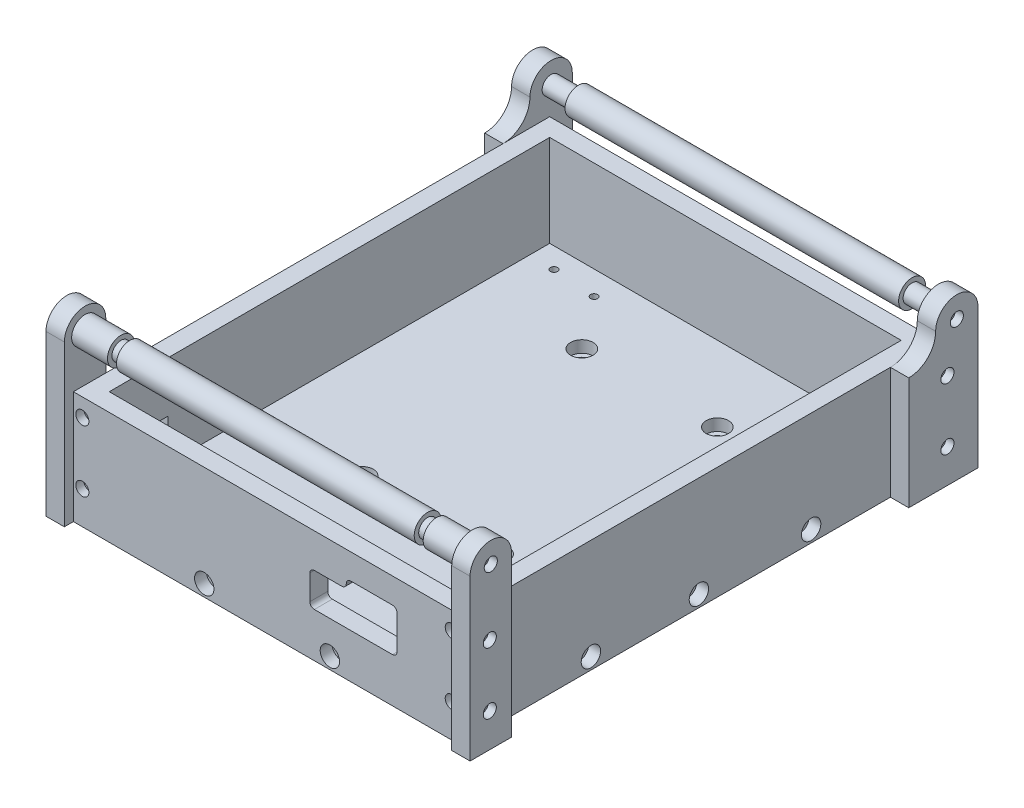
SolidWorks part; units mm, degrees
ref_plane "Front Plane" through (0, 0, 0) normal (0, 0, 1) x (1, 0, 0)
ref_plane "Top Plane" through (0, 0, 0) normal (0, 1, 0) x (1, 0, 0)
ref_plane "Right Plane" through (0, 0, 0) normal (1, 0, 0) x (0, 0, -1)
sketch "Sketch1" plane through (0, 0, 0) normal (0, 1, 0) x (1, 0, 0)
  line L1 (0, 0) -> (114.5, 0) construction
  line L2 (0, 0) -> (0, 146) construction
  line L3 (0, 146) -> (114.5, 146) construction
  line L4 (114.5, 0) -> (114.5, 146) construction
  line L8 (-5, 151) -> (119.5, 151)
  line L9 (119.5, -5) -> (119.5, 151)
  line L10 (-5, -5) -> (119.5, -5)
  line L11 (-5, -5) -> (-5, 151)
  line L12 (-11.35, 157.35) -> (125.85, 157.35)
  line L13 (125.85, -11.35) -> (125.85, 157.35)
  line L14 (-11.35, -11.35) -> (125.85, -11.35)
  line L15 (-11.35, -11.35) -> (-11.35, 157.35)
  dimension "D1" = 114.5
  dimension "D2" = 146
  dimension "D3" = 6.35
  dimension "D4" = 5
extrude "Boss-Extrude1" add sketch "Sketch1" against normal blind 6.35 contours L15 L12 L13 L14
sketch "Sketch3" plane through (0, 0, 0) normal (0, 1, 0) x (1, 0, 0)
  line L4 (-5, 151) -> (119.5, 151)
  line L5 (119.5, -5) -> (119.5, 151)
  line L6 (-5, -5) -> (119.5, -5)
  line L7 (-5, -5) -> (-5, 151)
  line L8 (-11.35, 157.35) -> (125.85, 157.35)
  line L9 (125.85, -11.35) -> (125.85, 157.35)
  line L10 (-11.35, -11.35) -> (125.85, -11.35)
  line L11 (-11.35, -11.35) -> (-11.35, 157.35)
  line L12 (-11.35, -11.35) -> (-11.35, 157.35) construction
  line L13 (-11.35, 157.35) -> (125.85, 157.35) construction
  line L14 (-11.35, -11.35) -> (125.85, -11.35) construction
  line L15 (-5, 151) -> (-11.35, 151) construction
  line L16 (-5, -5) -> (-11.35, -5) construction
  line L17 (119.5, -5) -> (125.85, -5) construction
  line L18 (119.5, 151) -> (125.85, 151) construction
  dimension "D1" = 6.35
  dimension "D2" = 6.35
  dimension "D3" = 6.35
  dimension "D4" = 6.35
extrude "Boss-Extrude2" add sketch "Sketch3" along normal blind 32.5 and the other way blind 7.35
sketch "Sketch4" plane through (0, 0, 11.35) normal (0, 0, 1) x (1, 0, 0)
  line L0 (-11.35, -7.35) -> (-11.35, 32.5) construction
  line L1 (-11.35, 32.5) -> (125.85, 32.5) construction
  line L3 (119.5, 0) -> (119.5, 32.5) construction
  line L4 (-5, 0) -> (119.5, 0) construction
  line L5 (-5, -7.35) -> (-5, -6.35) construction
  line L6 (119.5, -7.35) -> (119.5, -6.35) construction
  circle A0 centre (-8.175, 26.15) radius 1.1906 construction
  circle A2 centre (35, -3.175) radius 1.7859
  circle A3 centre (79.5, -3.175) radius 1.7859
  circle A4 centre (122.675, 26.15) radius 1.1906 construction
  circle A6 centre (-8.175, 4.325) radius 1.1906 construction
  circle A7 centre (122.675, 4.325) radius 1.1906 construction
  dimension "D2" = 2.3813
  dimension "D3" = 3.5719
  dimension "D1" = 3.175
  dimension "D4" = 6.35
  dimension "D6" = 3.175
  dimension "D7" = 21.825
  dimension "D8" = 3.175
  dimension "D9" = 40
  dimension "D10" = 40
hole_wizard "CBORE for #0 Socket Head Cap Screw1" positions "3DSketch1" profile "Sketch6" counterbore size "#0" standard "ANSI Inch"
sketch3d "3DSketch1"
  point P0 (-8.175, 26.15, 11.35)
  point P3 (-8.175, 4.325, 11.35)
  point P9 (122.675, 26.15, 11.35)
  point P12 (122.675, 4.325, 11.35)
sketch "Sketch6" plane through (-8.175, 26.15, 11.35) normal (1, 0, 0) x (0, -1, 0)
  line L0 (0, 0) -> (0, 10.7654)
  line L1 (0, 10.7654) -> (1.1906, 10.05)
  line L2 (1.1906, 10.05) -> (1.1906, 2.8448)
  line L3 (1.1906, 2.8448) -> (2.3241, 2.8448)
  line L4 (2.3241, 2.8448) -> (2.3241, 0)
  line L5 (2.3241, 0) -> (0, 0)
  line L10 (0, 10.7654) -> (-1.1906, 10.05) construction
  line L11 (0, -6.35) -> (0, 107.95) construction
  dimension "Hole Dia." = 2.3812
  dimension "Hole Depth" = 10.05
  dimension "C'Bore Dia." = 4.6482
  dimension "C'Bore Depth" = 2.8448
  dimension "Drill Angle" = 118
sketch "Sketch7" plane through (125.85, 0, 0) normal (1, 0, 0) x (0, 0, -1)
  line L0 (-5, 0) -> (-5, 32.5) construction
  line L1 (-11.35, -1.3891) -> (-11.35, -4.9609) construction
  line L2 (-5, 0) -> (151, 0) construction
  circle A0 centre (34.75, -3.175) radius 1.7859
  circle A1 centre (112.75, -3.175) radius 1.7859
  circle A2 centre (73, -3.175) radius 1.7859
  point P6 (-11.35, -3.175)
  point P11 (73, 0)
  dimension "D1" = 3.5719
  dimension "D3" = 39.75
  dimension "D4" = 39.75
hole_wizard "CBORE for #0 Socket Head Cap Screw2" positions "3DSketch2" profile "Sketch8" counterbore size "#0" standard "ANSI Inch"
sketch3d "3DSketch2"
  point P0 (125.85, -3.175, -34.75)
  point P3 (125.85, -3.175, -73)
  point P6 (125.85, -3.175, -112.75)
  point P10 (35, -3.175, 11.35)
  point P13 (79.5, -3.175, 11.35)
sketch "Sketch8" plane through (125.85, -3.175, -34.75) normal (0, 1, 0) x (0, 0, -1)
  line L0 (0, 0) -> (0, 11.1231)
  line L1 (0, 11.1231) -> (1.7859, 10.05)
  line L2 (1.7859, 10.05) -> (1.7859, 4.1656)
  line L3 (1.7859, 4.1656) -> (3.429, 4.1656)
  line L4 (3.429, 4.1656) -> (3.429, 0)
  line L5 (3.429, 0) -> (0, 0)
  line L10 (0, 11.1231) -> (-1.7859, 10.05) construction
  line L11 (0, -6.35) -> (0, 107.95) construction
  dimension "Hole Dia." = 3.5719
  dimension "Hole Depth" = 10.05
  dimension "C'Bore Dia." = 6.858
  dimension "C'Bore Depth" = 4.1656
  dimension "Drill Angle" = 118
sketch "Sketch9" plane through (125.85, 0, 0) normal (1, 0, 0) x (0, 0, -1)
  line L5 (-14.546, -7.35) -> (0.1332, -7.35)
  line L6 (-14.546, -7.35) -> (-14.546, 49.35)
  line L9 (140.825, -7.35) -> (157.35, -7.35)
  line L11 (157.35, -7.35) -> (157.35, 1.02) construction
  line L12 (157.35, -7.35) -> (157.35, 32.5) construction
  line L14 (-8.5052, 27.3406) -> (-8.5052, 24.9594) construction
  line L15 (-8.5052, 6.6491) -> (-8.5052, 2.0009) construction
  line L16 (-11.35, 32.5) -> (157.35, 32.5) construction
  line L20 (165.35, -7.35) -> (165.35, 42.025)
  line L21 (140.825, 32.5) -> (140.825, -7.35)
  line L22 (0.1332, -7.35) -> (0.1332, 49.35)
  line L23 (157.35, -7.35) -> (165.35, -7.35)
  circle A3 centre (-7.2064, 49.35) radius 3.175 construction
  arc A11 (140.825, 32.5) -> (150.35, 42.025) centre (140.825, 42.025) ccw
  circle A12 centre (157.85, 42.025) radius 3.175 construction
  arc A13 (150.35, 42.025) -> (165.35, 42.025) centre (157.85, 42.025) cw
  arc A14 (-14.546, 49.35) -> (0.1332, 49.35) centre (-7.2064, 49.35) cw
  point P18 (-8.5052, 26.15)
  point P19 (-8.5052, 4.325)
  point P22 (154.175, 26.15)
  point P25 (154.175, 4.325)
  dimension "D1" = 6.35
  dimension "D2" = 7.5
  dimension "D3" = 9.525
  dimension "D6" = 6.35
  dimension "D8" = 39.85
  dimension "D4" = 0.5
  dimension "D5" = 3.175
  dimension "D7" = 16.85
extrude "Boss-Extrude3" add sketch "Sketch9" along normal blind 6.4979
sketch "Sketch10" plane through (0, 0, 0) normal (0, 1, 0) x (1, 0, 0)
  line L0 (57.25, -5) -> (57.25, 50.041) construction
  line L1 (-5, -5) -> (119.5, -5) construction
ref_plane "Plane1" through (57.25, 0, 0) normal (1, 0, 0) x (0, 0, -1)
mirror "Mirror1" about plane through (57.25, 0, 0) normal (1, 0, 0) of "Boss-Extrude3"
sketch "Sketch11" plane through (-17.8479, 0, 0) normal (-1, 0, 0) x (0, 0, 1)
  circle A0 centre (7.2064, 49.35) radius 3.175
extrude "Boss-Extrude4" add sketch "Sketch11" against normal up to surface (150.1957 mm away) up to face at (132.3479, 22.8349, 7.2064)
sketch "Sketch13" plane through (132.3479, 0, 0) normal (1, 0, 0) x (0, 0, -1)
  circle A0 centre (157.85, 42.025) radius 3.175
  arc A1 (165.35, 42.025) -> (150.35, 42.025) centre (157.85, 42.025) ccw construction
  dimension "D1" = 6.35
extrude "Boss-Extrude5" add sketch "Sketch13" against normal up to surface (150.1957 mm away) up to face at (-17.8479, 21.4755, -152.9345)
sketch "Sketch15" plane through (132.3479, 0, 0) normal (1, 0, 0) x (0, 0, -1)
  circle A0 centre (157.85, 42.025) radius 4.7625
  arc A1 (165.35, 42.025) -> (150.35, 42.025) centre (157.85, 42.025) ccw construction
  dimension "D1" = 9.525
extrude "Boss-Extrude6" add sketch "Sketch15" against normal blind 118.15 from offset 15.85 offset against normal yes
hole_wizard "CBORE for #0 Socket Head Cap Screw3" positions "3DSketch3" profile "Sketch16" counterbore size "#0" standard "ANSI Inch"
sketch3d "3DSketch3"
  line L4 (132.3479, 49.35, 7.2064) -> (125.85, 49.35, 7.2064) construction
  line L5 (132.3479, 42.025, -157.85) -> (125.85, 42.025, -157.85) construction
  line L9 (132.3479, 49.35, 14.546) -> (132.3479, -7.35, 14.546) construction
  line L10 (132.3479, 49.35, 14.546) -> (132.3479, -7.35, 14.546)
  line L11 (132.3479, 32.5, -154.5249) -> (122.9136, 32.5, -154.5249) construction
  line L14 (119.5, 32.5, -151) -> (-5, 32.5, -151) construction
  point P17 (132.3479, 49.35, 7.2064)
  point P21 (132.3479, 42.025, -157.85)
  point P87 (132.3479, 26.3157, 7.5566)
  point P89 (132.3479, 4.5437, 7.5566)
  point P105 (132.3479, 26.3157, -154.5249)
  point P107 (132.3479, 4.5437, -154.5249)
  dimension "D1" = 3.5249
sketch "Sketch16" plane through (132.3479, 49.35, 7.2064) normal (0, 1, 0) x (0, 0, -1)
  line L0 (0, 0) -> (0, 10.7654)
  line L1 (0, 10.7654) -> (1.1906, 10.05)
  line L2 (1.1906, 10.05) -> (1.1906, 2.8448)
  line L3 (1.1906, 2.8448) -> (2.3241, 2.8448)
  line L4 (2.3241, 2.8448) -> (2.3241, 0)
  line L5 (2.3241, 0) -> (0, 0)
  line L10 (0, 10.7654) -> (-1.1906, 10.05) construction
  line L11 (0, -6.35) -> (0, 107.95) construction
  dimension "Hole Dia." = 2.3812
  dimension "Hole Depth" = 10.05
  dimension "C'Bore Dia." = 4.6482
  dimension "C'Bore Depth" = 2.8448
  dimension "Drill Angle" = 118
sketch "Sketch19" plane through (0, 0, 0) normal (0, 1, 0) x (1, 0, 0)
  line L0 (119.5, 151) -> (-5, 151) construction
  line L1 (14.51, 146.55) -> (99.99, 146.55) construction
  line L2 (14.51, 146.55) -> (14.51, 18.79) construction
  line L3 (14.51, 18.79) -> (99.99, 18.79) construction
  line L4 (99.99, 146.55) -> (99.99, 18.79) construction
  line L5 (57.25, -5) -> (57.25, 50.041) construction
  point P6 (33.0427, 124.3411)
  point P7 (81.0329, 124.3411)
  point P8 (81.0329, 46.5266)
  point P9 (33.0427, 46.5266)
  dimension "D1" = 4.45
  dimension "D2" = 85.48
  dimension "D3" = 127.76
  dimension "D4" = 42.74
hole_wizard "CBORE for #8 Socket Head Cap Screw1" positions "Sketch20" profile "Sketch21" counterbore size "#8" standard "ANSI Inch"
sketch "Sketch20" plane through (0, 0, 0) normal (0, 1, 0) x (1, 0, 0)
  point P0 (33.0427, 124.3411)
  point P3 (81.0329, 124.3411)
  point P6 (81.0329, 46.5266)
  point P9 (33.0427, 46.5266)
sketch "Sketch21" plane through (33.0427, 0, -124.3411) normal (1, 0, 0) x (0, 0, 1)
  line L0 (0, 0) -> (0, 11.4007)
  line L1 (0, 11.4007) -> (2.2479, 10.05)
  line L2 (2.2479, 10.05) -> (2.2479, 4.1656)
  line L3 (2.2479, 4.1656) -> (3.9688, 4.1656)
  line L4 (3.9688, 4.1656) -> (3.9688, 0)
  line L5 (3.9688, 0) -> (0, 0)
  line L10 (0, 11.4007) -> (-2.2479, 10.05) construction
  line L11 (0, -6.35) -> (0, 107.95) construction
  dimension "Hole Dia." = 4.4958
  dimension "Hole Depth" = 10.05
  dimension "C'Bore Dia." = 7.9375
  dimension "C'Bore Depth" = 4.1656
  dimension "Drill Angle" = 118
sketch "Sketch22" plane through (0, 0, 11.35) normal (0, 0, 1) x (1, 0, 0)
  line L0 (82.912, 18.778) -> (73.9904, 18.778) construction
  line L10 (57.25, 32.5) -> (57.25, -11.4472) construction
  line L11 (-11.35, 32.5) -> (125.85, 32.5) construction
  line L12 (82.912, 20.3655) -> (73.9904, 20.3655)
  line L13 (72.4029, 18.778) -> (72.4029, 9.9676)
  line L15 (-0.034, 5) -> (-0.034, 6.6) construction
  line L19 (114.52, 5) -> (114.52, 6.6) construction
  line L20 (-0.034, 6.6) -> (114.52, 6.6) construction
  line L21 (-0.034, 5) -> (114.52, 5) construction
  line L23 (73.9904, 8.3801) -> (101.668, 8.3801)
  line L26 (103.2555, 9.9676) -> (103.2555, 21.9697)
  line L27 (101.668, 23.5572) -> (86.89, 23.5572)
  line L28 (85.3025, 21.953) -> (85.3025, 21.9697)
  line L29 (82.912, 20.3655) -> (83.715, 20.3655)
  line L30 (119.5, 19.6927) -> (119.5, 3.1627) construction
  line L31 (125.85, -7.35) -> (125.85, 32.5) construction
  line L32 (14.51, 0) -> (99.99, 0) construction
  line L33 (73.9904, 18.778) -> (73.9904, 9.9676) construction
  line L34 (73.9904, 9.9676) -> (101.668, 9.9676) construction
  line L35 (101.668, 9.9676) -> (101.668, 21.9697) construction
  line L36 (101.668, 21.9697) -> (86.89, 21.9697) construction
  line L37 (86.89, 21.953) -> (86.89, 21.9697) construction
  line L38 (82.912, 18.778) -> (83.715, 18.778) construction
  arc A12 (73.9904, 20.3655) -> (72.4029, 18.778) centre (73.9904, 18.778) ccw
  arc A13 (72.4029, 9.9676) -> (73.9904, 8.3801) centre (73.9904, 9.9676) ccw
  arc A14 (103.2555, 9.9676) -> (101.668, 8.3801) centre (101.668, 9.9676) cw
  arc A15 (101.668, 23.5572) -> (103.2555, 21.9697) centre (101.668, 21.9697) cw
  arc A16 (86.89, 23.5572) -> (85.3025, 21.9697) centre (86.89, 21.9697) ccw
  arc A17 (83.715, 20.3655) -> (85.3025, 21.953) centre (83.715, 21.953) ccw
  arc A18 (73.9904, 18.778) -> (73.9904, 18.778) centre (73.9904, 18.778) ccw construction
  arc A19 (73.9904, 9.9676) -> (73.9904, 9.9676) centre (73.9904, 9.9676) ccw construction
  arc A20 (101.668, 9.9676) -> (101.668, 9.9676) centre (101.668, 9.9676) cw construction
  arc A21 (101.668, 21.9697) -> (101.668, 21.9697) centre (101.668, 21.9697) cw construction
  arc A22 (86.89, 21.9697) -> (86.89, 21.9697) centre (86.89, 21.9697) ccw construction
  arc A23 (83.715, 18.778) -> (86.89, 21.953) centre (83.715, 21.953) ccw construction
  point P7 (103.2555, 15.9686)
  point P10 (41.9707, 6.6)
  point P13 (42.0971, 20.3655)
  point P28 (0, 0)
  dimension "D5" = 5
  dimension "D1" = 114.554
  dimension "D2" = 6.35
  dimension "D3" = 4.98
  dimension "D4" = 1.6
  dimension "D6" = 16.9572
  dimension "D7" = 11.2645
  dimension "D8" = 42.1171
  dimension "D9" = 1.5875
extrude "Cut-Extrude1" cut sketch "Sketch22" against normal blind 10
sketch "Sketch24" plane through (-11.35, 0, 0) normal (1, 0, 0) x (0, 0, -1)
  circle A0 centre (-7.2064, 49.35) radius 4.7625
  dimension "D1" = 9.525
extrude "Boss-Extrude7" add sketch "Sketch24" along normal blind 12.7
sketch "Sketch25" plane through (1.35, 0, 0) normal (1, 0, 0) x (0, 0, -1)
  circle A0 centre (-7.2064, 49.35) radius 4.7625
  dimension "D1" = 9.525
extrude "Boss-Extrude8" add sketch "Sketch25" along normal blind 52.73 from offset 3.175 contours A0
mirror "Mirror2" about plane through (57.255, 49.35, 7.2064) normal (1, 0, 0) of "Boss-Extrude8", "Boss-Extrude7"
sketch "Sketch26" plane through (132.3479, 0, 0) normal (1, 0, 0) x (0, 0, -1)
  point P0 (-7.5566, 26.3157)
  point P1 (-7.5566, 4.5437)
  point P3 (-67.572, 30.3007)
sketch "Sketch27" plane through (0, 0, 0) normal (0, 1, 0) x (1, 0, 0)
  line L0 (-0.025, -1.548) -> (114.529, -1.548) construction
  line L1 (-0.025, 147.55) -> (-0.025, -1.548) construction
  line L2 (21.9633, 146.6989) -> (92.003, 146.6989) construction
  line L3 (21.9633, 146.6989) -> (21.9633, 138.5739) construction
  line L4 (21.9633, 138.5739) -> (92.003, 138.5739) construction
  line L5 (92.003, 146.6989) -> (92.003, 138.5739) construction
  line L6 (-0.025, 147.55) -> (114.529, 147.55) construction
  line L7 (114.529, 147.55) -> (114.529, -1.548) construction
  line L8 (-5, 151) -> (-5, -5) construction
  line L9 (114.529, 147.55) -> (110.719, 147.55) construction
  line L10 (114.529, 147.55) -> (114.529, 143.74) construction
  line L11 (114.529, 143.74) -> (110.719, 143.74) construction
  line L12 (110.719, 147.55) -> (110.719, 143.74) construction
  line L13 (114.529, -1.548) -> (110.719, -1.548) construction
  line L14 (114.529, -1.548) -> (114.529, 2.262) construction
  line L15 (114.529, 2.262) -> (110.719, 2.262) construction
  line L16 (110.719, -1.548) -> (110.719, 2.262) construction
  line L18 (119.5, 151) -> (-5, 151) construction
  circle A0 centre (3.785, 143.74) radius 1.25
  circle A1 centre (19.176, 142.55) radius 1.25
  circle A2 centre (95.175, 142.55) radius 1.25
  circle A3 centre (110.719, 143.74) radius 1.25
  circle A4 centre (19.176, 24.55) radius 1.25
  circle A5 centre (95.175, 24.55) radius 1.25
  circle A6 centre (110.719, 2.262) radius 1.25
  point P21 (1.9194, 7.5829)
  point P22 (-0.025, 15.4347)
  dimension "D1" = 149.098
  dimension "D2" = 114.554
  dimension "D3" = 19.201
  dimension "D4" = 26.098
  dimension "D5" = 19.201
  dimension "D6" = 3.81
  dimension "D7" = 3.81
  dimension "D8" = 5
  dimension "D9" = 19.354
  dimension "D10" = 3.81
  dimension "D11" = 19.354
  dimension "D12" = 8.125
  dimension "D13" = 70.0397
  dimension "D14" = 21.9883
  dimension "D15" = 0.8511
  dimension "D16" = 4.975
  dimension "D17" = 3.45
extrude "Cut-Extrude3" cut sketch "Sketch27" against normal blind 10
sketch "Sketch28" plane through (-11.35, 0, 0) normal (-1, 0, 0) x (0, 0, 1)
  line L0 (5, 0) -> (-50.041, 0) construction
  line L1 (-0.85, 6.6) -> (-15.85, 6.6)
  line L2 (-0.85, 6.6) -> (-0.85, 14.6)
  line L3 (-0.85, 14.6) -> (-15.85, 14.6)
  line L4 (-15.85, 6.6) -> (-15.85, 14.6)
  line L5 (5, 0) -> (5, 32.5) construction
  line L6 (5, 0) -> (5, 32.5) construction
  line L7 (4.15, 4.6854) -> (4.15, 1.7852) construction
  line L8 (-2.0406, 7.7906) -> (-2.0406, 13.4094) construction
  line L9 (-2.0406, 13.4094) -> (-14.6594, 13.4094) construction
  line L10 (-14.6594, 7.7906) -> (-14.6594, 13.4094) construction
  line L11 (-2.0406, 7.7906) -> (-14.6594, 7.7906) construction
  line L12 (-2.4375, 8.1875) -> (-2.4375, 13.0125) construction
  line L13 (-2.4375, 13.0125) -> (-14.2625, 13.0125) construction
  line L14 (-14.2625, 8.1875) -> (-14.2625, 13.0125) construction
  line L15 (-2.4375, 8.1875) -> (-14.2625, 8.1875) construction
  point P0 (1.548, 0)
  point P2 (-7.5829, 0)
  point P4 (-15.4347, 0)
  dimension "D1" = 15
  dimension "D2" = 0.85
  dimension "D3" = 6.6
  dimension "D4" = 8
  dimension "D5" = 5
  dimension "D6" = 1.1906
  dimension "D7" = 1.5875
extrude "Cut-Extrude4" cut sketch "Sketch28" against normal blind 10
equation "\"D6@Sketch4\"=\"D1@Sketch4\""
equation "\"D8@Sketch4\"=\"D1@Sketch4\""
equation "\"D4@Sketch19\"=\"D2@Sketch19\"/2"
equation "\"D3@Sketch7\"=\"D3@Sketch7\""
equation "\"D4@Sketch7\"=\"D3@Sketch7\""
